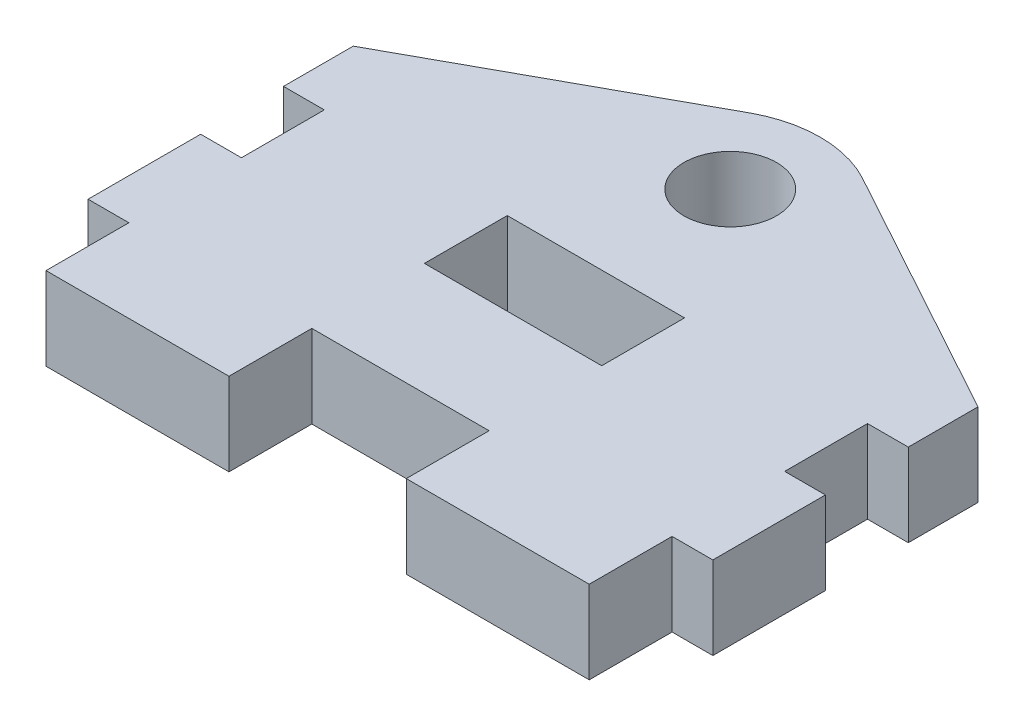
SolidWorks part; units mm, degrees
ref_plane "Front Plane" through (0, 0, 0) normal (0, 0, 1) x (1, 0, 0)
ref_plane "Top Plane" through (0, 0, 0) normal (0, 1, 0) x (1, 0, 0)
ref_plane "Right Plane" through (0, 0, 0) normal (1, 0, 0) x (0, 0, -1)
sketch "Sketch1" plane through (0, 0, 0) normal (0, 1, 0) x (1, 0, 0)
  line L0 (-25.6, 7.9375) -> (-25.6, 0) construction
  line L1 (0, 0) -> (-6.45, 0)
  line L2 (0, 0) -> (0, 7.9375)
  line L3 (0, 7.9375) -> (-6.45, 7.9375)
  line L4 (-50.8, 0) -> (-50.8, 7.9375)
  line L5 (-44.75, 0) -> (-50.8, 0)
  line L6 (-50.8, 3.9687) -> (0, 3.9688) construction
  line L7 (-44.75, 0) -> (-44.75, -5.842)
  line L8 (-44.75, -5.842) -> (-31.85, -5.842)
  line L9 (-31.85, 0) -> (-31.85, -5.842)
  line L10 (-19.35, 0) -> (-19.35, -5.842)
  line L11 (-6.45, -5.842) -> (-19.35, -5.842)
  line L12 (-6.45, 0) -> (-6.45, -5.842)
  line L13 (-6.45, 7.9375) -> (-6.45, 13.7795)
  line L14 (-19.35, 13.7795) -> (-31.85, 13.7795)
  line L15 (-19.35, 7.9375) -> (-19.35, 13.7795)
  line L16 (-31.85, 7.9375) -> (-31.85, 13.7795)
  line L17 (-44.75, 13.7795) -> (-50.8, 13.7795)
  line L18 (-44.75, 7.9375) -> (-44.75, 13.7795)
  line L19 (-19.35, 0) -> (-31.85, 0)
  line L20 (-19.35, 7.9375) -> (-31.85, 7.9375)
  line L21 (-44.75, 7.9375) -> (-50.8, 7.9375)
  line L23 (-0.4, 13.7795) -> (-6.45, 13.7795)
  line L24 (-0.4, 13.7795) -> (-0.4, 16.9545)
  line L25 (-25.6, 7.9375) -> (-25.6, 24.5097) construction
  line L26 (-50.8, 13.7795) -> (-50.8, 16.9545)
  line L30 (-50.8, 16.9545) -> (-29.5976, 28.5775)
  line L33 (-0.4, 16.9545) -> (-21.6024, 28.5775)
  arc A0 (-29.5976, 28.5775) -> (-21.6024, 28.5775) centre (-25.6, 21.2852) cw
  dimension "D1" = 7.9375
  dimension "D2" = 50.8
  dimension "D3" = 5.842
  dimension "D4" = 12.9
  dimension "D5" = 6.25
  dimension "D6" = 3.175
extrude "Boss-Extrude2" add sketch "Sketch1" along normal blind 5.842
hole_wizard "F (0.257) Diameter Hole1" positions "Sketch3" profile "Sketch2" hole size "F" standard "ANSI Inch" end condition through all
sketch "Sketch3" plane through (0, 5.842, 0) normal (0, 1, 0) x (1, 0, 0)
  arc A4 (-21.6024, 28.5775) -> (-29.5976, 28.5775) centre (-25.6, 21.2852) ccw construction
  point P26 (-25.6, 23.2513)
  point P34 (-25.6, 29.6013)
  dimension "D1" = 6.35
sketch "Sketch2" plane through (-25.6, 5.842, -23.2513) normal (1, 0, 0) x (0, 0, 1)
  line L0 (0, 0) -> (0, 5.842)
  line L1 (0, 5.842) -> (3.2639, 5.842)
  line L2 (3.2639, 5.842) -> (3.2639, 0)
  line L5 (3.2639, 0) -> (0, 0)
  line L11 (0, -6.35) -> (0, 107.95) construction
  dimension "Thru Hole Dia." = 6.5278
  dimension "Thru Hole Depth" = 5.842
sketch "Sketch4" plane through (0, 5.842, 0) normal (0, 1, 0) x (1, 0, 0)
  line L1 (-50.8, 0) -> (-44.75, 0) construction
  line L2 (-50.8, 7.9375) -> (-47.625, 7.9375)
  line L3 (-50.8, 7.9375) -> (-50.8, 0)
  line L4 (-50.8, 0) -> (-47.625, 0)
  line L7 (-47.625, 7.9375) -> (-47.625, 0)
  line L8 (-3.575, 7.9375) -> (-3.575, 0)
  line L9 (-0.4, 0) -> (-3.575, 0)
  line L11 (-0.4, 7.9375) -> (-3.575, 7.9375)
  line L12 (-50.8, 13.7795) -> (-47.625, 13.7795)
  line L13 (-0.4, 7.9375) -> (0, 7.9375)
  line L14 (-50.8, 13.7795) -> (-50.8, 20.1295)
  line L15 (-0.4, 0) -> (0, 0)
  line L16 (0, 7.9375) -> (0, 0)
  line L17 (-47.625, 13.7795) -> (-47.625, 20.1295)
  line L18 (-47.625, 20.1295) -> (-50.8, 20.1295)
  line L19 (-0.4, 20.1295) -> (-3.575, 20.1295)
  line L20 (-3.575, 13.7795) -> (-3.575, 20.1295)
  line L21 (-0.4, 13.7795) -> (-3.575, 13.7795)
  line L22 (-0.4, 13.7795) -> (-0.4, 20.1295)
  dimension "D1" = 3.175
  dimension "D2" = 6.35
  dimension "D3" = 6.35
extrude "Cut-Extrude1" cut sketch "Sketch4" against normal through all
